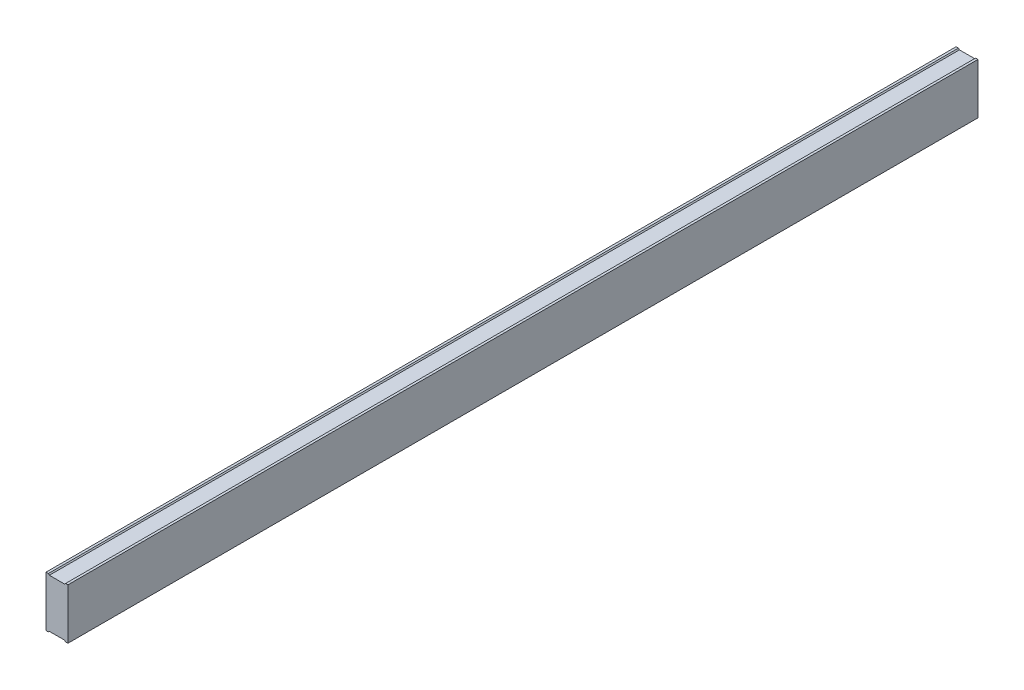
SolidWorks part; units mm, degrees
material "6061-T6 (SS)"
ref_plane "前视基准面" through (0, 0, 0) normal (0, 0, 1) x (1, 0, 0)
ref_plane "上视基准面" through (0, 0, 0) normal (0, 1, 0) x (1, 0, 0)
ref_plane "右视基准面" through (0, 0, 0) normal (1, 0, 0) x (0, 0, -1)
sketch "Model" plane through (0, 0, 0) normal (0, 0, 1) x (1, 0, 0)
  line L0 (11746.24, -58203.4132) -> (11636.4348, -58203.4132) construction
  line L1 (11739.24, -58278.4132) -> (11736.24, -58275.4132)
  line L11 (11746.24, -58128.4132) -> (11746.24, -58278.4132)
  line L12 (11739.24, -58128.4132) -> (11746.24, -58128.4132)
  line L13 (11739.24, -58128.4132) -> (11736.24, -58131.4132)
  line L14 (11691.24, -58131.4132) -> (11736.24, -58131.4132)
  line L15 (11688.24, -58128.4132) -> (11691.24, -58131.4132)
  line L16 (11688.24, -58128.4132) -> (11681.24, -58128.4132)
  line L17 (11681.24, -58128.4132) -> (11681.24, -58136.4132)
  line L18 (11681.24, -58136.4132) -> (11739.24, -58136.4132)
  line L19 (11742.24, -58139.4132) -> (11742.24, -58267.4132)
  line L20 (11739.24, -58278.4132) -> (11746.24, -58278.4132)
  line L23 (11681.24, -58270.4132) -> (11739.24, -58270.4132)
  line L24 (11681.24, -58278.4132) -> (11681.24, -58270.4132)
  line L25 (11688.24, -58278.4132) -> (11681.24, -58278.4132)
  line L26 (11688.24, -58278.4132) -> (11691.24, -58275.4132)
  line L27 (11691.24, -58275.4132) -> (11736.24, -58275.4132)
  arc A2 (11742.24, -58139.4132) -> (11739.24, -58136.4132) centre (11739.24, -58139.4132) ccw
  arc A3 (11742.24, -58267.4132) -> (11739.24, -58270.4132) centre (11739.24, -58267.4132) cw
  point P12 (11742.24, -58203.4132)
  point P16 (11742.74, -58278.4132)
  dimension "D8" = 3
  dimension "D1" = 150
  dimension "D2" = 4
  dimension "D3" = 65
  dimension "D4" = 8
  dimension "D5" = 7
  dimension "D6" = 10
  dimension "D7" = 5
extrude "凸台-拉伸1" add sketch "Model" along normal blind 2697 contours L11 L20 L1 L27 L26 L25 L24 L23 A3 L19 A2 L18 L17 L16 L15 L14 L13 L12
sketch "草图2" plane through (0, 0, 2697) normal (0, 0, 1) x (1, 0, 0)
  line L0 (11681.24, -58270.4132) -> (11739.24, -58270.4132) construction
  line L1 (11681.24, -58136.4132) -> (11742.24, -58136.4132)
  line L2 (11681.24, -58136.4132) -> (11681.24, -58270.4132)
  line L3 (11681.24, -58270.4132) -> (11742.24, -58270.4132)
  line L4 (11742.24, -58136.4132) -> (11742.24, -58270.4132)
  line L5 (11742.24, -58139.4132) -> (11742.24, -58267.4132) construction
extrude "凸台-拉伸2" add sketch "草图2" against normal blind 6
sketch "草图3" plane through (0, 0, 0) normal (0, 0, -1) x (-1, 0, 0)
  line L0 (-11681.24, -58270.4132) -> (-11739.24, -58270.4132) construction
  line L1 (-11681.24, -58136.4132) -> (-11742.24, -58136.4132)
  line L2 (-11681.24, -58136.4132) -> (-11681.24, -58270.4132)
  line L3 (-11681.24, -58270.4132) -> (-11742.24, -58270.4132)
  line L4 (-11742.24, -58136.4132) -> (-11742.24, -58270.4132)
  line L5 (-11742.24, -58139.4132) -> (-11742.24, -58267.4132) construction
extrude "凸台-拉伸3" add sketch "草图3" against normal blind 6
sketch "Sketch1" [suppressed] plane through (11742.24, 0, 0) normal (-1, 0, 0) x (0, 0, 1)
  line L3 (2697, -58278.4132) -> (0, -58278.4132) construction
  line L4 (0, -58128.4132) -> (0, -58278.4132) construction
  circle A0 centre (200, -58203.4132) radius 8
  dimension "D1" = 16
  dimension "D2" = 75
  dimension "D3" = 200
extrude "TX1" [suppressed] cut sketch "Sketch1" against normal up to next
sketch "Sketch2" [suppressed] plane through (11742.24, 0, 0) normal (-1, 0, 0) x (0, 0, 1)
  line L1 (2697, -58278.4132) -> (0, -58278.4132) construction
  circle A0 centre (291.0708, -58203.4132) radius 8
  circle A4 centre (200, -58203.4132) radius 8 construction
  dimension "D1" = 16
  dimension "D2" = 75
  dimension "D3" = 91.0708
extrude "TX2" [suppressed] cut sketch "Sketch2" against normal up to next
sketch "Sketch3" [suppressed] plane through (11742.24, 0, 0) normal (-1, 0, 0) x (0, 0, 1)
  line L0 (2697, -58278.4132) -> (0, -58278.4132) construction
  circle A0 centre (365.0595, -58203.4132) radius 8
  circle A1 centre (291.0708, -58203.4132) radius 8 construction
  dimension "D1" = 16
  dimension "D2" = 75
  dimension "D3" = 73.9888
extrude "TX3" [suppressed] cut sketch "Sketch3" against normal up to next
sketch "Sketch4" [suppressed] plane through (11742.24, 0, 0) normal (-1, 0, 0) x (0, 0, 1)
  line L0 (2697, -58278.4132) -> (0, -58278.4132) construction
  circle A0 centre (424.5978, -58203.4132) radius 8
  circle A1 centre (365.0595, -58203.4132) radius 8 construction
  dimension "D1" = 16
  dimension "D2" = 75
  dimension "D3" = 59.5383
extrude "TX4" [suppressed] cut sketch "Sketch4" against normal up to next
sketch "Sketch5" [suppressed] plane through (11742.24, 0, 0) normal (-1, 0, 0) x (0, 0, 1)
  line L0 (2697, -58278.4132) -> (0, -58278.4132) construction
  circle A0 centre (478.6266, -58203.4132) radius 8
  circle A1 centre (424.5978, -58203.4132) radius 8 construction
  dimension "D1" = 16
  dimension "D2" = 75
  dimension "D3" = 54.0288
extrude "TX5" [suppressed] cut sketch "Sketch5" against normal up to next
sketch "Sketch6" [suppressed] plane through (11742.24, 0, 0) normal (-1, 0, 0) x (0, 0, 1)
  line L0 (2697, -58278.4132) -> (0, -58278.4132) construction
  circle A0 centre (522.1086, -58203.4132) radius 8
  circle A1 centre (478.6266, -58203.4132) radius 8 construction
  dimension "D1" = 16
  dimension "D2" = 75
  dimension "D3" = 43.482
extrude "TX6" [suppressed] cut sketch "Sketch6" against normal up to next
sketch "Sketch7" [suppressed] plane through (11742.24, 0, 0) normal (-1, 0, 0) x (0, 0, 1)
  line L0 (2697, -58278.4132) -> (0, -58278.4132) construction
  circle A0 centre (565.3355, -58203.4132) radius 8
  circle A1 centre (522.1086, -58203.4132) radius 8 construction
  dimension "D1" = 16
  dimension "D2" = 75
  dimension "D3" = 43.2269
extrude "TX7" [suppressed] cut sketch "Sketch7" against normal up to next
sketch "Sketch8" [suppressed] plane through (11742.24, 0, 0) normal (-1, 0, 0) x (0, 0, 1)
  line L0 (2697, -58278.4132) -> (0, -58278.4132) construction
  circle A0 centre (611.3964, -58203.4132) radius 8
  circle A1 centre (565.3355, -58203.4132) radius 8 construction
  dimension "D1" = 16
  dimension "D2" = 75
  dimension "D3" = 46.061
extrude "TX8" [suppressed] cut sketch "Sketch8" against normal up to next
sketch "Sketch9" plane through (0, -58131.4132, 0) normal (0, 1, 0) x (1, 0, 0)
  line L0 (11746.24, -2697) -> (11746.24, 0) construction
  line L1 (11691.24, -2697) -> (11736.24, -2697) construction
  circle A0 centre (11713.74, -2643.0533) radius 8
  dimension "D1" = 16
  dimension "D2" = 32.5
  dimension "D3" = 53.9467
extrude "FLX1" [suppressed] cut sketch "Sketch9" against normal up to next
sketch "Sketch10" [suppressed] plane through (0, -58131.4132, 0) normal (0, 1, 0) x (1, 0, 0)
  line L0 (11746.24, -2697) -> (11746.24, 0) construction
  circle A0 centre (11713.74, -2592.8025) radius 8
  circle A1 centre (11713.74, -2643.0533) radius 8 construction
  dimension "D1" = 16
  dimension "D2" = 32.5
  dimension "D3" = 50.2509
extrude "FLX2" [suppressed] cut sketch "Sketch10" against normal up to next
sketch "Sketch11" plane through (0, -58131.4132, 0) normal (0, 1, 0) x (1, 0, 0)
  line L0 (11746.24, -2697) -> (11746.24, 0) construction
  line L1 (11691.24, 0) -> (11736.24, 0) construction
  circle A0 centre (11713.74, -50) radius 8
  dimension "D1" = 16
  dimension "D2" = 32.5
  dimension "D3" = 50
extrude "FRX1" [suppressed] cut sketch "Sketch11" against normal up to next
sketch "Sketch12" [suppressed] plane through (0, -58131.4132, 0) normal (0, 1, 0) x (1, 0, 0)
  line L0 (11746.24, -2697) -> (11746.24, 0) construction
  circle A0 centre (11713.74, -104.5155) radius 8
  circle A1 centre (11713.74, -50) radius 8 construction
  dimension "D1" = 16
  dimension "D2" = 32.5
  dimension "D3" = 54.5155
extrude "FRX2" [suppressed] cut sketch "Sketch12" against normal up to next
